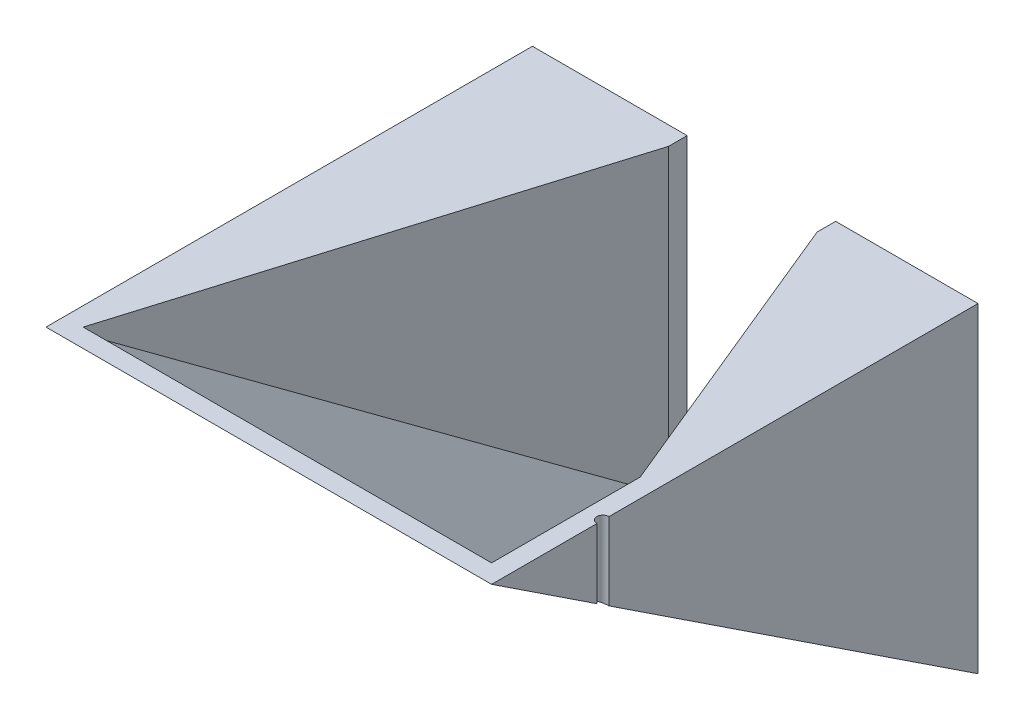
SolidWorks part; units mm, degrees
ref_plane "Front Plane" through (0, 0, 0) normal (0, 0, 1) x (1, 0, 0)
ref_plane "Top Plane" through (0, 0, 0) normal (0, 1, 0) x (1, 0, 0)
ref_plane "Right Plane" through (0, 0, 0) normal (1, 0, 0) x (0, 0, -1)
sketch "Sketch6" plane through (0, 0, 0) normal (1, 0, 0) x (0, 0, -1)
  line L0 (0, 0) -> (65.5, 0)
  line L1 (65.5, -43.1758) -> (0, 0)
  line L2 (65.5, 0) -> (65.5, -43.1758)
  line L3 (0, 0) -> (0, -2.1656) construction
  line L4 (0, -2.1656) -> (45.5, -2.1656) construction
  line L5 (45.5, 0) -> (45.5, -29.9924) construction
  dimension "D1" = 65.5
  dimension "D2" = 78.45
  dimension "D3" = 45.5
  dimension "D4" = 33.392
extrude "Boss-Extrude3" add sketch "Sketch6" along normal blind 60
sketch "Sketch8" plane through (0, 0, 0) normal (0, 1, 0) x (1, 0, 0)
  line L0 (0, 2.5) -> (2.5, 2.5) construction
  line L1 (0, 65.5) -> (0, 0) construction
  line L2 (2.5, 2.5) -> (2.5, 0) construction
  line L3 (60, 0) -> (0, 0) construction
  line L4 (2.5, 65.5) -> (2.5, 63) construction
  line L5 (60, 65.5) -> (0, 65.5) construction
  line L6 (2.5, 63) -> (0, 63) construction
  line L7 (57.5, 65.5) -> (57.5, 63) construction
  line L8 (57.5, 63) -> (60, 63) construction
  line L9 (60, 65.5) -> (60, 0) construction
  line L10 (57.5, 0) -> (57.5, 2.5) construction
  line L11 (57.5, 2.5) -> (60, 2.5) construction
  line L12 (2.5, 63) -> (2.5, 2.5)
  line L13 (2.5, 2.5) -> (57.5, 2.5)
  line L14 (57.5, 2.5) -> (57.5, 63)
  line L15 (57.5, 63) -> (2.5, 63)
  dimension "D1" = 2.5
  dimension "D2" = 2.5
  dimension "D3" = 2.5
  dimension "D4" = 2.5
  dimension "D5" = 2.5
  dimension "D6" = 2.5
  dimension "D7" = 2.5
  dimension "D8" = 2.5
extrude "Cut-Extrude1" cut sketch "Sketch8" against normal up to next
sketch "Sketch9" plane through (2.5, 0, 0) normal (1, 0, 0) x (0, 0, -1)
  line L0 (2.5, -1.6479) -> (2.5, -0.824)
  line L1 (2.5, -1.6479) -> (2.5, 0) construction
  line L2 (2.5, -0.824) -> (63, -40.7079)
  line L3 (63, -41.5279) -> (63, 0) construction
  line L4 (63, -40.7079) -> (63, -41.5279)
  line L5 (63, -41.5279) -> (2.5, -1.6479)
  dimension "D1" = 0.824
  dimension "D2" = 0.82
extrude "Boss-Extrude4" add sketch "Sketch9" along normal blind 56
sketch "Sketch11" plane through (0, 0, 0) normal (0, 1, 0) x (1, 0, 0)
  line L1 (57.5, 63) -> (57.5, 22.5)
  line L3 (2.5, 63) -> (2.5, 2.5)
  line L5 (57.5, 2.5) -> (57.5, 63) construction
  line L8 (2.5, 63) -> (20.8346, 63)
  line L9 (57.5, 63) -> (2.5, 63) construction
  line L10 (20.8346, 63) -> (2.5, 2.5)
  line L12 (57.5, 63) -> (2.5, 63) construction
  line L14 (20.8346, 63) -> (40.8346, 63) construction
  line L15 (57.5, 22.5) -> (40.8346, 63)
  line L16 (40.8346, 63) -> (57.5, 63)
  line L18 (57.5, 2.5) -> (2.5, 2.5) construction
  dimension "D1" = 20
  dimension "D2" = 20
extrude "Boss-Extrude7" add sketch "Sketch11" against normal up to next
sketch "Sketch13" plane through (0, 0, -63) normal (0, 0, 1) x (1, 0, 0)
  line L0 (20.8346, 0) -> (40.8346, 0)
  line L1 (20.8346, -40.7079) -> (20.8346, 0) construction
  line L2 (40.8346, 0) -> (40.8346, -40.7079)
  line L3 (40.8346, -40.7079) -> (20.8346, -40.7079)
  line L4 (20.8346, -40.7079) -> (20.8346, 0)
  dimension "D1" = 20
  dimension "D2" = 40.7079
extrude "Cut-Extrude7" cut sketch "Sketch13" against normal blind 3
sketch "Sketch18" plane through (0, 0, 0) normal (0, 1, 0) x (1, 0, 0)
  line L1 (60, 65.5) -> (60, 0) construction
  line L2 (60, 0) -> (60, 15) construction
  circle A1 centre (60, 15) radius 0.815
  dimension "D1" = 1.63
  dimension "D2" = 15
extrude "Cut-Extrude10" cut sketch "Sketch18" against normal through all both
